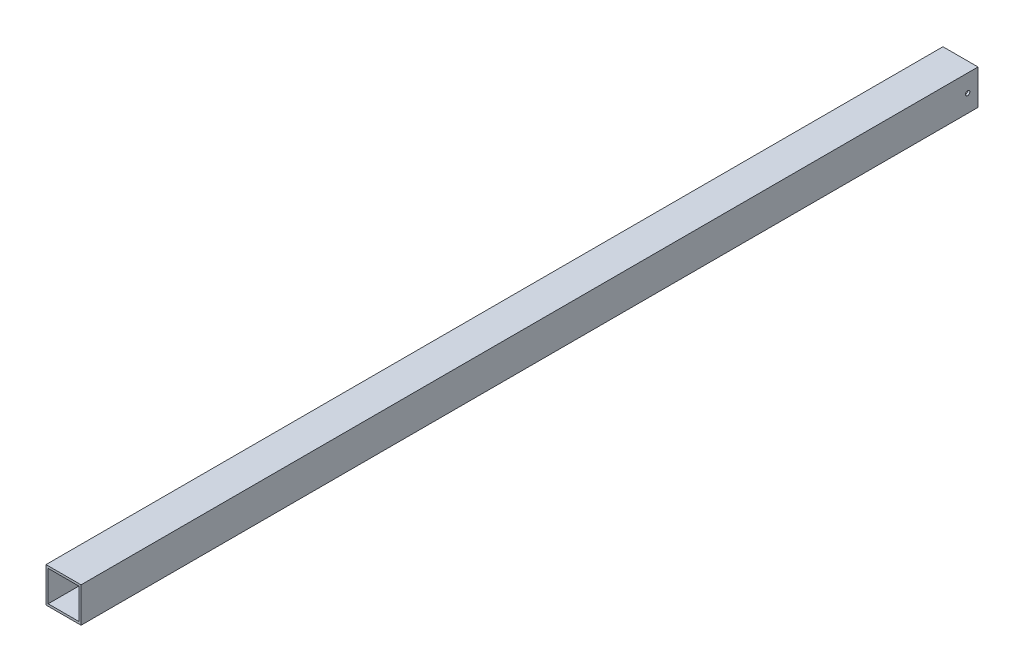
SolidWorks part; units mm, degrees
ref_plane "Plan de face" through (0, 0, 0) normal (0, 0, 1) x (1, 0, 0)
ref_plane "Plan de dessus" through (0, 0, 0) normal (0, 1, 0) x (1, 0, 0)
ref_plane "Plan de droite" through (0, 0, 0) normal (1, 0, 0) x (0, 0, -1)
sketch "Esquisse2" plane through (0, 0, 0) normal (0, 0, 1) x (1, 0, 0)
  line L1 (-25.4, 25.4) -> (25.4, 25.4)
  line L2 (-25.4, 25.4) -> (-25.4, -25.4)
  line L3 (-25.4, -25.4) -> (25.4, -25.4)
  line L4 (25.4, 25.4) -> (25.4, -25.4)
  line L5 (-25.4, 25.4) -> (25.4, -25.4) construction
  line L6 (-25.4, -25.4) -> (25.4, 25.4) construction
  line L7 (-22.225, 22.225) -> (22.225, 22.225)
  line L8 (-22.225, 22.225) -> (-22.225, -22.225)
  line L9 (-22.225, -22.225) -> (22.225, -22.225)
  line L10 (22.225, 22.225) -> (22.225, -22.225)
  line L11 (-22.225, 22.225) -> (22.225, -22.225) construction
  line L12 (-22.225, -22.225) -> (22.225, 22.225) construction
  point P0 (0, 0)
  point P6 (0, 0)
  dimension "D1" = 50.8
  dimension "D2" = 3.175
  dimension "D3" = 3.175
extrude "Boss.-Extru.1" add sketch "Esquisse2" along normal mid plane 1300
sketch "Esquisse4" plane through (-25.4, 0, 0) normal (-1, 0, 0) x (0, 0, 1)
  line L0 (650, 25.4) -> (-650, 25.4) construction
  line L3 (-650, 25.4) -> (-650, -25.4) construction
  circle A0 centre (-635, 0) radius 3.175
  dimension "D1" = 6.35
  dimension "D2" = 25.4
  dimension "D3" = 15
extrude "Enlèv. mat.-Extru.2" cut sketch "Esquisse4" against normal through all
hole_wizard "M4 Clearance Hole1" positions "Sketch1" profile "Sketch2" hole size "M4" standard "ANSI Metric"
sketch "Sketch1" plane through (-25.4, 0, 0) normal (-1, 0, 0) x (0, 0, 1)
  point P0 (517.1, -3.175)
  point P3 (557.1, -3.175)
  point P6 (597.1, -3.175)
sketch "Sketch2" plane through (-25.4, -3.175, 517.1) normal (0, 1, 0) x (0, 0, 1)
  line L0 (0, 0) -> (0, 3.175)
  line L1 (0, 3.175) -> (2.25, 3.175)
  line L2 (2.25, 3.175) -> (2.25, 0.175)
  line L3 (2.25, 0.175) -> (2.425, 0)
  line L5 (2.425, 0) -> (0, 0)
  line L6 (-2.25, 0.175) -> (-2.425, 0) construction
  line L11 (0, -6.35) -> (0, 107.95) construction
  dimension "Thru Hole Dia." = 4.5
  dimension "Thru Hole Depth" = 3.175
  dimension "Near C'Sink Dia." = 4.85
  dimension "Near C'Sink Angle" = 90
equation "\"D1@Boss.-Extru.1\"=1300mm"
